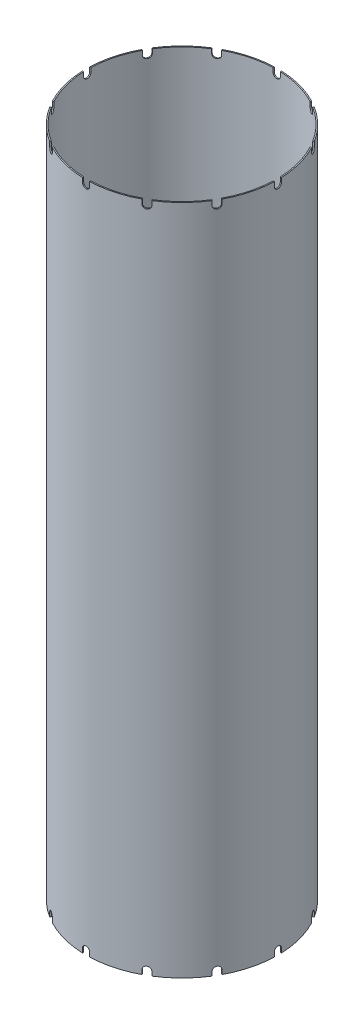
SolidWorks part; units mm, degrees
material "Hexcel AS4C (3000 Filaments)"
ref_plane "Front Plane" through (0, 0, 0) normal (0, 0, 1) x (1, 0, 0)
ref_plane "Top Plane" through (0, 0, 0) normal (0, 1, 0) x (1, 0, 0)
ref_plane "Right Plane" through (0, 0, 0) normal (1, 0, 0) x (0, 0, -1)
sketch "Sketch1" plane through (0, 0, 0) normal (0, 1, 0) x (1, 0, 0)
  circle A0 centre (0, 0) radius 83.439
  circle A1 centre (0, 0) radius 84.455
  dimension "D1" = 168.91
  dimension "D2" = 1.016
extrude "Boss-Extrude1" add sketch "Sketch1" along normal blind 591.2018
ref_plane "Plane1" through (0, 295.6009, 0) normal (0, 1, 0) x (1, 0, 0)
sketch "Sketch2" plane through (0, 0, 0) normal (0, 0, 1) x (1, 0, 0)
  line L0 (0, 3.81) -> (0, -68.0288) construction
  line L1 (3.175, 3.81) -> (3.175, -68.0288)
  line L2 (-3.175, 3.81) -> (-3.175, -68.0288)
  line L3 (-84.455, 0) -> (84.455, 0) construction
  arc A0 (3.175, 3.81) -> (-3.175, 3.81) centre (0, 3.81) ccw
  arc A1 (-3.175, -68.0288) -> (3.175, -68.0288) centre (0, -68.0288) ccw
  point P3 (0, -32.1094)
  point P8 (0, 38.0889)
  dimension "D2" = 6.35
  dimension "D1" = 3.81
extrude "Cut-Extrude1" cut sketch "Sketch2" against normal through all
pattern_circular "CirPattern1" count 12 over 360 about axis through (0, 0, 0) along (0, 1, 0) of "Cut-Extrude1"
mirror "Mirror1" about plane through (0, 295.6009, 0) normal (0, 1, 0) of "CirPattern1", "Cut-Extrude1"
equation "\"nominalLength\" = 24in"
equation "\"interfaceOffset\" = 0.36217in"
equation "\"sheetLength\"= \"nominalLength\" - 2 * \"interfaceOffset\""
equation "\"D1@Boss-Extrude1\"=\"sheetLength\""
